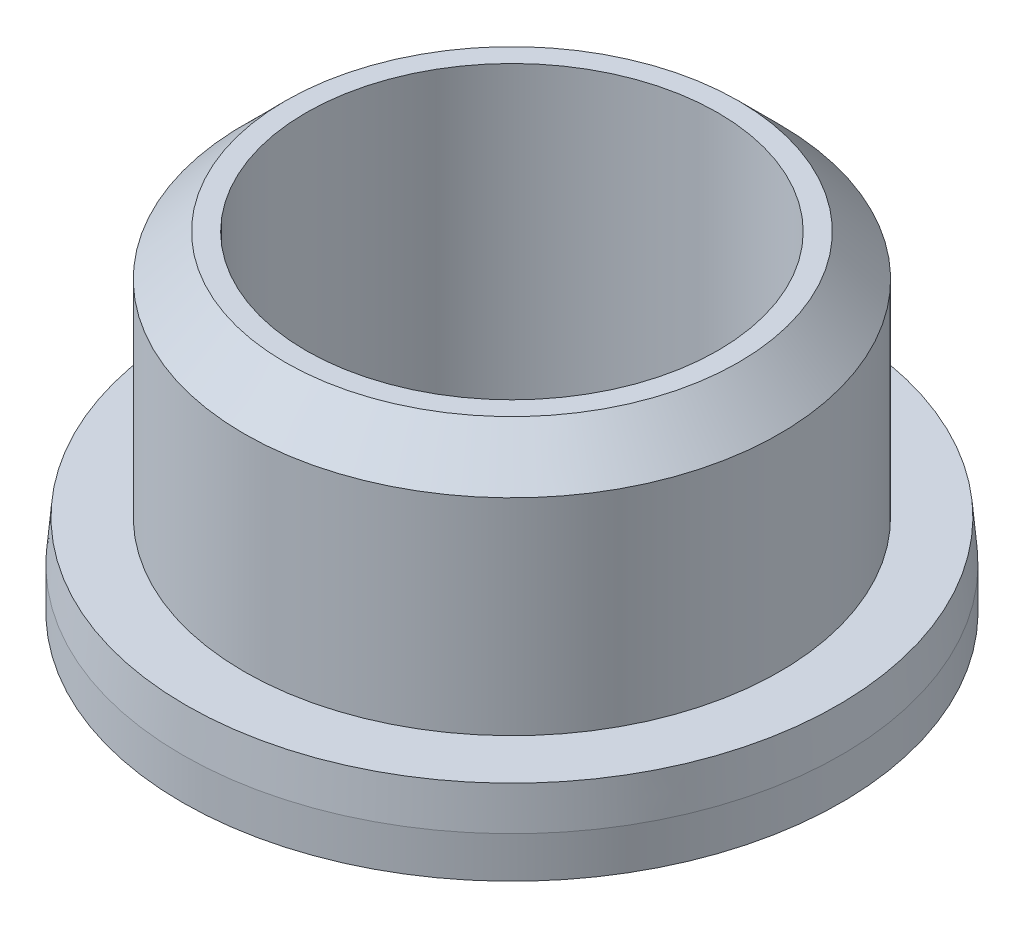
SolidWorks part; units mm, degrees
ref_plane "Front Plane" through (0, 0, 0) normal (0, 0, 1) x (1, 0, 0)
ref_plane "Top Plane" through (0, 0, 0) normal (0, 1, 0) x (1, 0, 0)
ref_plane "Right Plane" through (0, 0, 0) normal (1, 0, 0) x (0, 0, -1)
sketch "Sketch1" plane through (0, 0, 0) normal (0, 1, 0) x (1, 0, 0)
  circle A0 centre (0, 0) radius 8
  dimension "D1" = 16
extrude "Boss-Extrude1" add sketch "Sketch1" along normal blind 2
sketch "Sketch2" plane through (0, 2, 0) normal (0, 1, 0) x (1, 0, 0)
  circle A0 centre (0, 0) radius 6.5
  dimension "D1" = 13
extrude "Boss-Extrude2" add sketch "Sketch2" along normal blind 6
sketch "Sketch3" plane through (0, 8, 0) normal (0, 1, 0) x (1, 0, 0)
  circle A0 centre (0, 0) radius 5
  dimension "D1" = 10
extrude "Cut-Extrude1" cut sketch "Sketch3" against normal blind 8
chamfer "Chamfer1" distance 1 angle 45 1 edges at (0, 8, 6.5)
chamfer "Chamfer2" distance 1 angle 5 1 edges at (0, 2, 8)
